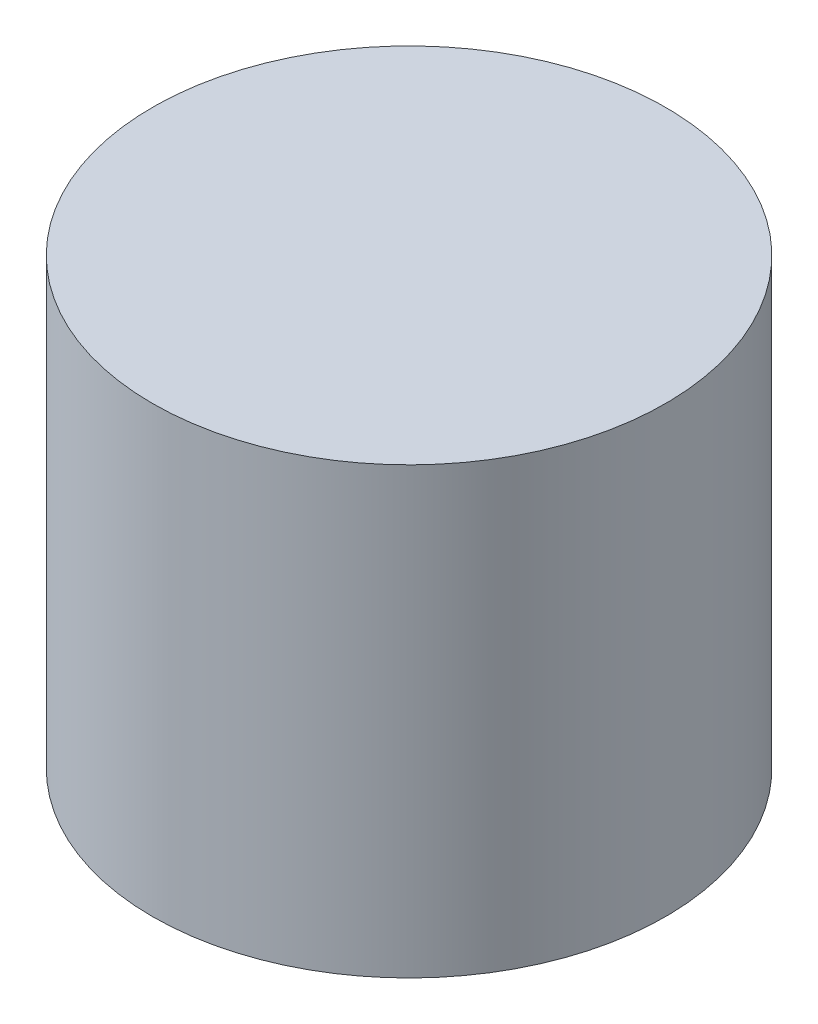
SolidWorks part; units mm, degrees
ref_plane "Front" through (0, 0, 0) normal (0, 0, 1) x (1, 0, 0)
ref_plane "Top" through (0, 0, 0) normal (0, 1, 0) x (1, 0, 0)
ref_plane "Right" through (0, 0, 0) normal (1, 0, 0) x (0, 0, -1)
sketch "草图1" plane through (0, 0, 0) normal (0, 1, 0) x (1, 0, 0)
  circle A0 centre (0, 0) radius 6.35
  dimension "D1" = 12.7
extrude "凸台-拉伸1" add sketch "草图1" along normal blind 11
